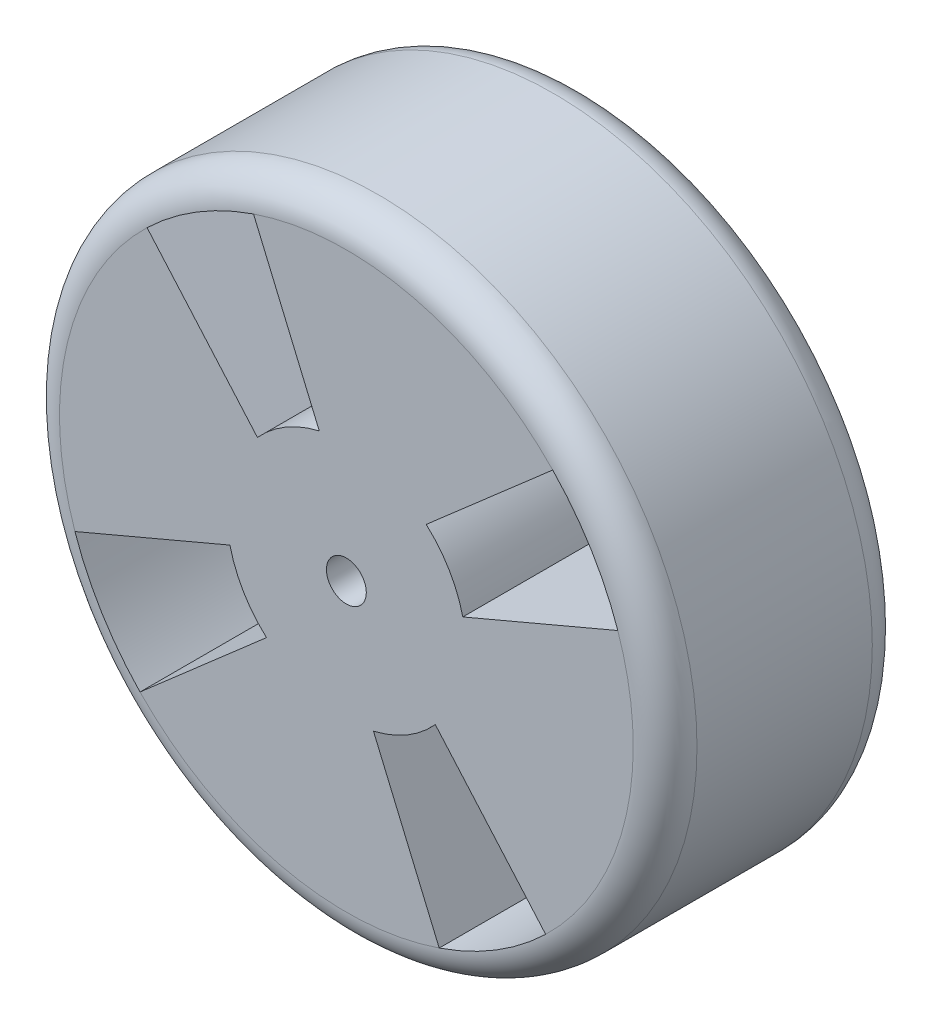
SolidWorks part; units mm, degrees
ref_plane "Front Plane" through (0, 0, 0) normal (0, 0, 1) x (1, 0, 0)
ref_plane "Top Plane" through (0, 0, 0) normal (0, 1, 0) x (1, 0, 0)
ref_plane "Right Plane" through (0, 0, 0) normal (1, 0, 0) x (0, 0, -1)
sketch "Sketch2" plane through (0, 0, 0) normal (0, 0, 1) x (1, 0, 0)
  circle A0 centre (0, 0) radius 101.6
  dimension "D1" = 203.2
extrude "Boss-Extrude1" add sketch "Sketch2" against normal blind 76.2
fillet "Fillet1" radius 10.16 2 edges at (101.6, 0, -76.2) (101.6, 0, 0)
sketch "Sketch3" plane through (0, 0, 0) normal (0, 0, 1) x (1, 0, 0)
  circle A0 centre (0, 0) radius 6.35
  dimension "D1" = 12.7
extrude "Cut-Extrude1" cut sketch "Sketch3" against normal up to next
sketch "Sketch4" plane through (0, 0, 0) normal (0, 0, 1) x (1, 0, 0)
  circle A0 centre (0, 0) radius 38.1
  dimension "D1" = 76.2
sketch "Sketch5" plane through (0, 0, 0) normal (0, 0, 1) x (1, 0, 0)
  line L0 (1.5914, 91.4262) -> (-2.0486, 38.0449)
  line L1 (40.2521, 82.1039) -> (20.132, 32.3467)
  line L2 (65.7733, 63.5228) -> (25.4532, 28.3504)
  line L3 (86.5187, 29.5937) -> (37.1081, 8.6371)
  line L4 (91.4262, -1.5914) -> (38.0449, 2.0486)
  line L5 (82.1039, -40.2521) -> (32.3467, -20.132)
  line L6 (63.5228, -65.7733) -> (28.3504, -25.4532)
  line L7 (29.5937, -86.5187) -> (8.6371, -37.1081)
  line L8 (-1.5914, -91.4262) -> (2.0486, -38.0449)
  line L9 (-40.2521, -82.1039) -> (-20.132, -32.3467)
  line L10 (-65.7733, -63.5228) -> (-25.4532, -28.3504)
  line L11 (-86.5187, -29.5937) -> (-37.1081, -8.6371)
  line L12 (-91.4262, 1.5914) -> (-38.0449, -2.0486)
  line L13 (-82.1039, 40.2521) -> (-32.3467, 20.132)
  line L14 (-63.5228, 65.7733) -> (-28.3504, 25.4532)
  line L15 (-29.5937, 86.5187) -> (-8.6371, 37.1081)
  arc A0 (-2.0486, 38.0449) -> (20.132, 32.3467) centre (0, 0) cw
  circle A1 centre (0, 0) radius 38.1 construction
  arc A2 (1.5914, 91.4262) -> (40.2521, 82.1039) centre (0, 0) cw
  circle A3 centre (0, 0) radius 91.44 construction
  arc A4 (65.7733, 63.5228) -> (86.5187, 29.5937) centre (0, 0) cw
  arc A5 (25.4532, 28.3504) -> (37.1081, 8.6371) centre (0, 0) cw
  arc A6 (91.4262, -1.5914) -> (82.1039, -40.2521) centre (0, 0) cw
  arc A7 (38.0449, 2.0486) -> (32.3467, -20.132) centre (0, 0) cw
  arc A8 (63.5228, -65.7733) -> (29.5937, -86.5187) centre (0, 0) cw
  arc A9 (28.3504, -25.4532) -> (8.6371, -37.1081) centre (0, 0) cw
  arc A10 (-1.5914, -91.4262) -> (-40.2521, -82.1039) centre (0, 0) cw
  arc A11 (2.0486, -38.0449) -> (-20.132, -32.3467) centre (0, 0) cw
  arc A12 (-65.7733, -63.5228) -> (-86.5187, -29.5937) centre (0, 0) cw
  arc A13 (-25.4532, -28.3504) -> (-37.1081, -8.6371) centre (0, 0) cw
  arc A14 (-91.4262, 1.5914) -> (-82.1039, 40.2521) centre (0, 0) cw
  arc A15 (-38.0449, -2.0486) -> (-32.3467, 20.132) centre (0, 0) cw
  arc A16 (-63.5228, 65.7733) -> (-29.5937, 86.5187) centre (0, 0) cw
  arc A17 (-28.3504, 25.4532) -> (-8.6371, 37.1081) centre (0, 0) cw
  dimension "D1" = 22.1806
  dimension "D2" = 8
extrude "Cut-Extrude2" cut sketch "Sketch5" against normal up to next contours A5 L3 A4 L2 | L10 A13 L11 A12 | L6 A9 L7 A8 | L14 A17 L15 A16
